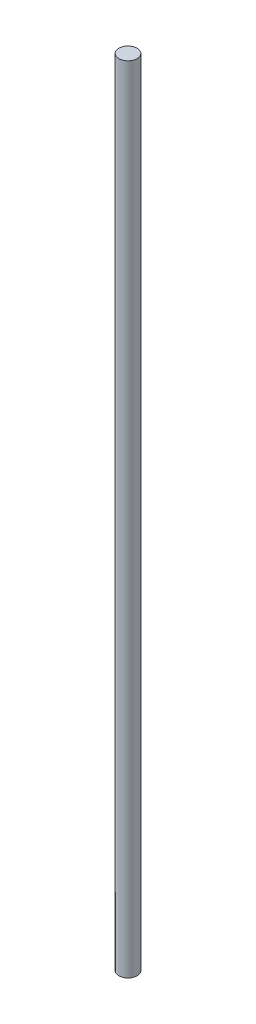
SolidWorks part; units mm, degrees
ref_plane "Front Plane" through (0, 0, 0) normal (0, 0, 1) x (1, 0, 0)
ref_plane "Top Plane" through (0, 0, 0) normal (0, 1, 0) x (1, 0, 0)
ref_plane "Right Plane" through (0, 0, 0) normal (1, 0, 0) x (0, 0, -1)
sketch "Sketch1" plane through (0, 0, 0) normal (0, 1, 0) x (1, 0, 0)
  circle A0 centre (0, 0) radius 4
  dimension "D1" = 8
extrude "Boss-Extrude1" add sketch "Sketch1" along normal blind 350
equation "\"Y-ROD-SPACING\"=75"
equation "\"Y-BED-OFFSET\"=2"
equation "\"Y-BED-ROD-INSET\"=3.5"
equation "\"T-SLOT-NUT-FILLET-RADIUS\"=0.5"
equation "\"T-SLOT-SCREW-SHAFT-RADIUS\"=1.55"
equation "\"T-SLOT-SCREW-SHAFT-CUTOUT-LENGTH\"=11"
equation "\"T-SLOT-NUT-DEPTH\"=3.5"
equation "\"T-SLOT-NUT-WIDTH\"=2.85"
equation "\"T-SLOT-NUT-END-DISTANCE\"=8"
equation "\"ACRYLIC-THICKNESS\"=10"
equation "\"ACRYLIC-TAB-CUTOUT-SIZE\"=\"ACRYLIC-THICKNESS\"+\"ACRYLIC-TAB-TOLERANCE\"*2"
equation "\"ACRYLIC-TAB-WIDTH\"=\"ACRYLIC-THICKNESS\""
equation "\"ACRYLIC-M3-HOLE\"=2.9"
equation "\"SMOOTHROD-CAP-SCREW-DISTANCE\"=20"
equation "\"FRAME-WIDTH-INNER\"=370"
equation "\"NEMA17-HOLE-SPACING\"=31"
equation "\"NEMA17-CENTRAL-CUTOUT\"=22.5"
equation "\"Z-BRACKET-REACH\"=57"
equation "\"TOP-BRACKET-SPACING\"=40"
equation "\"SMOOTHROD-X-LENGTH\"=350"
equation "\"SMOOTHROD-Y-LENGTH\"=350"
equation "\"SMOOTHROD-Z-LENGTH\"=350"
equation "\"SMOOTHROD-TIGHTENING-HEADROOM\"=.25"
equation "\"LEADSCREW-Z-LENGTH\"=300"
equation "\"D1@Boss-Extrude1\"=\"SMOOTHROD-X-LENGTH\""
